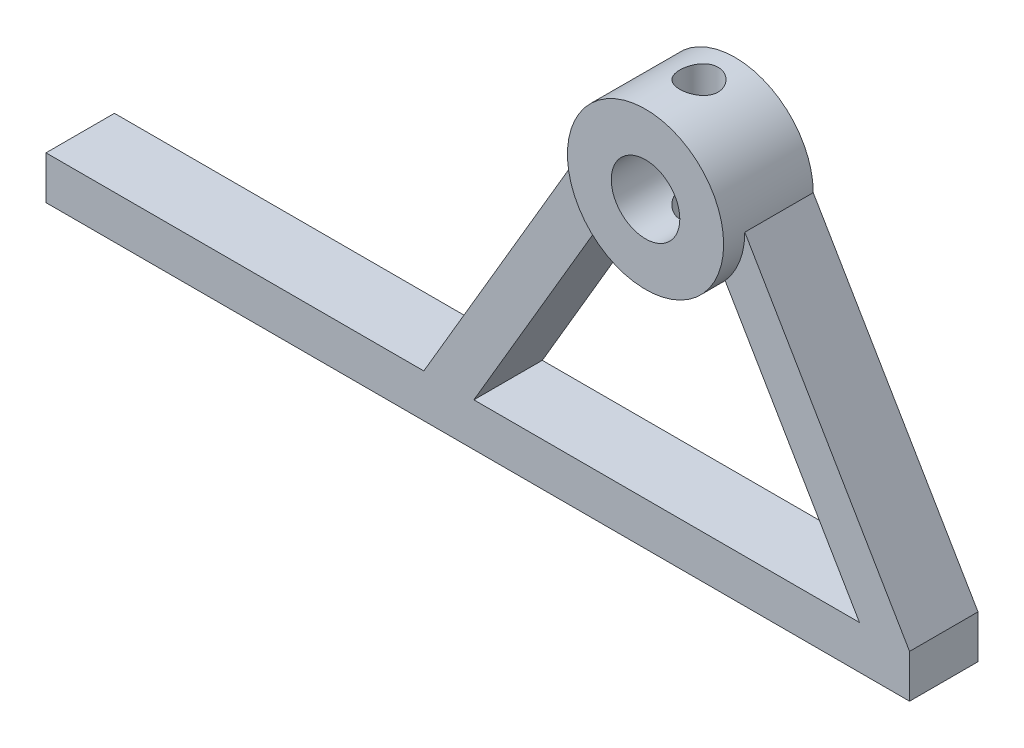
SolidWorks part; units mm, degrees
ref_plane "Front Plane" through (0, 0, 0) normal (0, 0, 1) x (1, 0, 0)
ref_plane "Top Plane" through (0, 0, 0) normal (0, 1, 0) x (1, 0, 0)
ref_plane "Right Plane" through (0, 0, 0) normal (1, 0, 0) x (0, 0, -1)
sketch "Sketch1" plane through (0, 0, 0) normal (0, 0, 1) x (1, 0, 0)
  line L0 (-22.5, -17.68) -> (-7.2357, 8.32)
  line L1 (-22.5, -21.68) -> (22.5, -21.68)
  line L2 (-22.5, -21.68) -> (-22.5, -17.68)
  line L4 (22.5, -21.68) -> (22.5, -17.68)
  line L5 (22.5, -17.68) -> (7.2357, 8.32)
  line L6 (-2.7983, 9.82) -> (2.7983, 9.82)
  line L7 (-2.7983, 6.82) -> (2.7983, 6.82)
  line L8 (17.8616, -17.68) -> (3.1138, 7.4402)
  line L9 (-17.8616, -17.68) -> (-3.1138, 7.4402)
  line L10 (-17.8616, -17.68) -> (-17.8616, -17.68)
  line L11 (-17.8616, -17.68) -> (17.8616, -17.68)
  line L12 (17.8616, -17.68) -> (17.8616, -17.68)
  circle A1 centre (0, 8.32) radius 3.175
  arc A2 (3.1138, 7.4402) -> (-3.1138, 7.4402) centre (0, 8.32) ccw
  circle A3 centre (0, 8.32) radius 7.2357
  arc A4 (7.2357, 8.32) -> (-7.2357, 8.32) centre (0, 8.32) ccw construction
  point P21 (0, -21.68)
  point P26 (0, -17.68)
  dimension "D1" = 6.35
  dimension "D8" = 14.4714
  dimension "D2" = 1.5
  dimension "D3" = 1.5
  dimension "D4" = 4
  dimension "D5" = 4
  dimension "D6" = 30
  dimension "D7" = 45
  dimension "D9" = 8.32
extrude "Boss-Extrude1" add sketch "Sketch1" along normal blind 6.34 contours A3 L9 A2 L8 | A3 L0 L2 L1 L4 L5 L8 L11 L9 | A1
ref_plane "Plane1" through (0, 14.32, 0) normal (0, 1, 0) x (1, 0, 0)
sketch "Sketch2" plane through (0, 14.32, 0) normal (0, 1, 0) x (1, 0, 0)
  line L0 (7.2357, 0) -> (-7.2357, 0) construction
  circle A0 centre (0, -3.35) radius 1.775
  dimension "D1" = 3.55
  dimension "D2" = 3.35
extrude "Cut-Extrude1" cut sketch "Sketch2" against normal blind 18.34 and the other way blind 4.34
sketch "Sketch3" plane through (0, 0, 0) normal (0, 0, -1) x (-1, 0, 0)
  circle A0 centre (0, 8.32) radius 7.2357
  circle A1 centre (0, 8.32) radius 3.175 construction
  circle A2 centre (0, 8.32) radius 3.175 construction
  arc A3 (7.2357, 8.32) -> (-7.2357, 8.32) centre (0, 8.32) ccw construction
  arc A4 (7.2357, 8.32) -> (-7.2357, 8.32) centre (0, 8.32) ccw construction
sketch "Sketch4" plane through (0, 0, 6.34) normal (0, 0, 1) x (1, 0, 0)
  line L0 (22.5, -21.68) -> (22.5, -17.68) construction
  line L1 (-17.8616, -17.68) -> (17.8616, -17.68) construction
  line L2 (-22.5, -21.68) -> (22.5, -21.68) construction
  line L3 (-22.5, -21.68) -> (-22.5, -17.68) construction
  line L4 (22.5, -21.68) -> (22.5, -17.68) construction
  line L5 (-17.8616, -17.68) -> (17.8616, -17.68) construction
  line L6 (-22.5, -21.68) -> (22.5, -21.68) construction
  line L7 (-22.5, -21.68) -> (-22.5, -17.68) construction
  line L9 (-22.5, -21.68) -> (22.5, -21.68)
  line L10 (-22.5, -21.68) -> (-22.5, -17.68)
  line L11 (-22.5, -17.68) -> (22.5, -17.68)
  line L12 (22.5, -21.68) -> (22.5, -17.68)
sketch "Sketch5" plane through (0, 0, 6.34) normal (0, 0, 1) x (1, 0, 0)
  circle A0 centre (0, 8.32) radius 7.2357 construction
  circle A1 centre (0, 8.32) radius 3.175 construction
  circle A2 centre (0, 8.32) radius 7.2357
  circle A3 centre (0, 8.32) radius 3.175
extrude "Boss-Extrude2" add sketch "Sketch5" along normal blind 1.96 contours A2 | A3
sketch "Sketch6" plane through (-22.5, 0, 0) normal (-1, 0, 0) x (0, 0, 1)
  line L4 (0, -17.68) -> (0, -21.68)
  line L5 (0, -21.68) -> (6.34, -21.68)
  line L6 (6.34, -21.68) -> (6.34, -17.68)
  line L7 (6.34, -17.68) -> (0, -17.68)
  line L8 (0, -17.68) -> (0, -21.68)
  line L9 (0, -21.68) -> (6.34, -21.68)
  line L10 (6.34, -21.68) -> (6.34, -17.68)
  line L11 (6.34, -17.68) -> (0, -17.68)
  dimension "D1" = 0
extrude "Boss-Extrude3" add sketch "Sketch6" along normal blind 35
